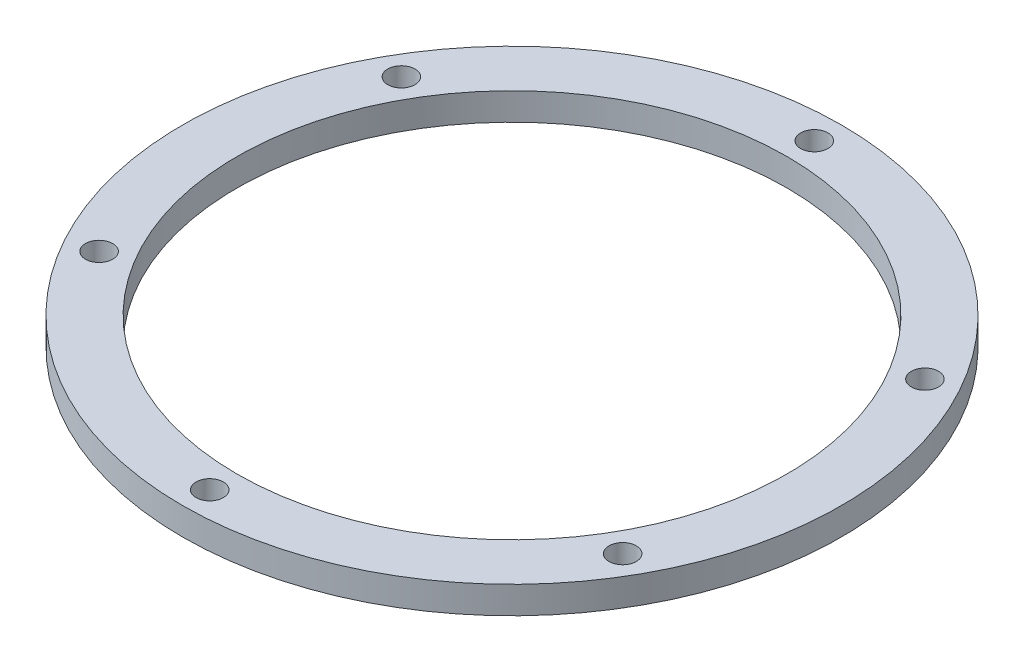
SolidWorks part; units mm, degrees
ref_plane "Front Plane" through (0, 0, 0) normal (0, 0, 1) x (1, 0, 0)
ref_plane "Top Plane" through (0, 0, 0) normal (0, 1, 0) x (1, 0, 0)
ref_plane "Right Plane" through (0, 0, 0) normal (1, 0, 0) x (0, 0, -1)
sketch "Sketch1" plane through (0, 0, 0) normal (0, 1, 0) x (1, 0, 0)
  circle A0 centre (0, 0) radius 30.25
  circle A1 centre (0, 0) radius 36.25
  dimension "D1" = 6
  dimension "D2" = 72.5
extrude "Boss-Extrude1" add sketch "Sketch1" along normal blind 3
sketch "Sketch2" plane through (0, 3, 0) normal (0, 1, 0) x (1, 0, 0)
  line L0 (0, 36.25) -> (0, 30.25) construction
  circle A0 centre (0, 0) radius 36.25 construction
  circle A1 centre (0, 0) radius 30.25 construction
  circle A2 centre (0, 33.25) radius 1.5
  dimension "D1" = 3
extrude "Cut-Extrude1" cut sketch "Sketch2" against normal through all both and the other way through all
pattern_circular "CirPattern1" count 6 every 60 about axis through (0, 0, 0) along (0, 1, 0) of "Cut-Extrude1"
